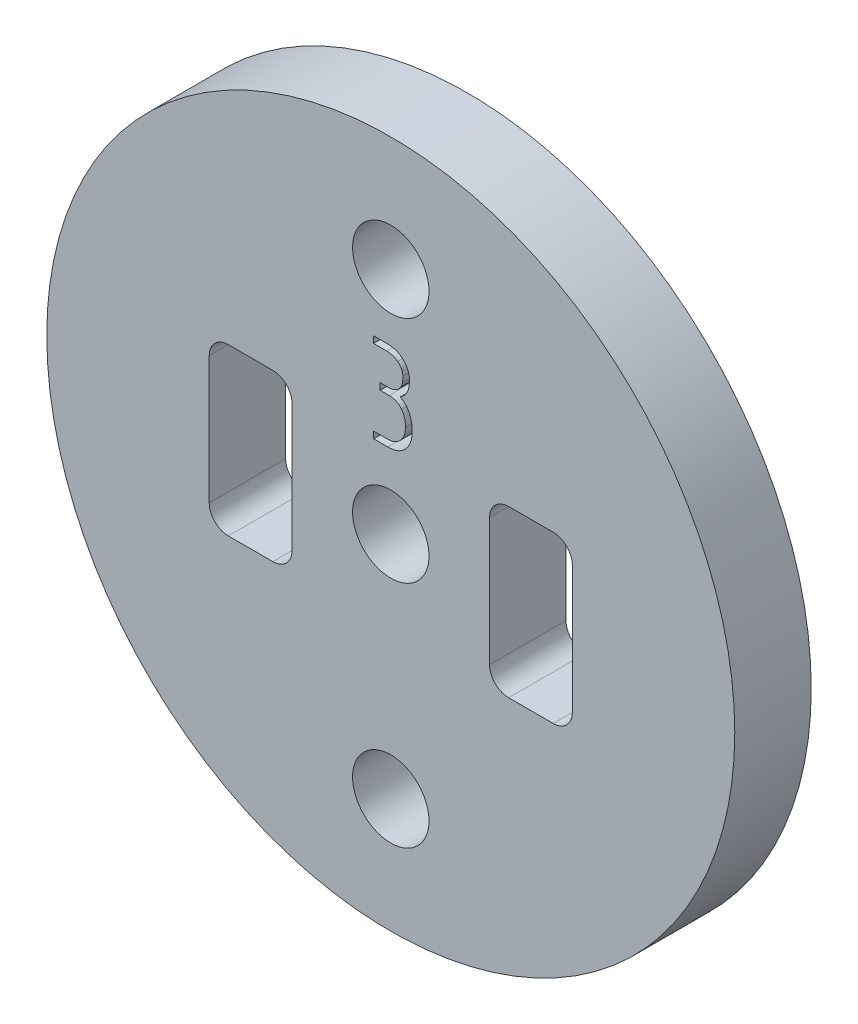
SolidWorks part; units mm, degrees
ref_plane "Alzado" through (0, 0, 0) normal (0, 0, 1) x (1, 0, 0)
ref_plane "Planta" through (0, 0, 0) normal (0, 1, 0) x (1, 0, 0)
ref_plane "Vista lateral" through (0, 0, 0) normal (1, 0, 0) x (0, 0, -1)
sketch "Model" plane through (0, 0, 0) normal (0, 0, 1) x (1, 0, 0)
  line L0 (27.5429, 287.087) -> (25.7929, 287.087)
  line L1 (28.2929, 281.337) -> (28.2929, 286.337)
  line L2 (25.7929, 280.587) -> (27.5429, 280.587)
  line L3 (25.0429, 286.337) -> (25.0429, 281.337)
  line L4 (14.7929, 287.087) -> (16.5429, 287.087)
  line L5 (14.0429, 281.337) -> (14.0429, 286.337)
  line L6 (16.5429, 280.587) -> (14.7929, 280.587)
  line L7 (17.2929, 286.337) -> (17.2929, 281.337)
  circle A0 centre (21.1679, 283.837) radius 1.5
  arc A1 (25.7929, 287.087) -> (25.0429, 286.337) centre (25.7929, 286.337) ccw
  arc A2 (28.2929, 286.337) -> (27.5429, 287.087) centre (27.5429, 286.337) ccw
  arc A3 (27.5429, 280.587) -> (28.2929, 281.337) centre (27.5429, 281.337) ccw
  arc A4 (25.0429, 281.337) -> (25.7929, 280.587) centre (25.7929, 281.337) ccw
  arc A5 (17.2929, 286.337) -> (16.5429, 287.087) centre (16.5429, 286.337) ccw
  arc A6 (14.7929, 287.087) -> (14.0429, 286.337) centre (14.7929, 286.337) ccw
  arc A7 (14.0429, 281.337) -> (14.7929, 280.587) centre (14.7929, 281.337) ccw
  arc A8 (16.5429, 280.587) -> (17.2929, 281.337) centre (16.5429, 281.337) ccw
  circle A9 centre (21.1679, 292.837) radius 1.5
  circle A10 centre (21.1679, 274.837) radius 1.5
  circle A11 centre (21.1679, 283.837) radius 13.5
  text T0 "3" font "SOLID EDGE ISO" height 3.5
extrude "Saliente-Extruir1" add sketch "Model" along normal blind 3
